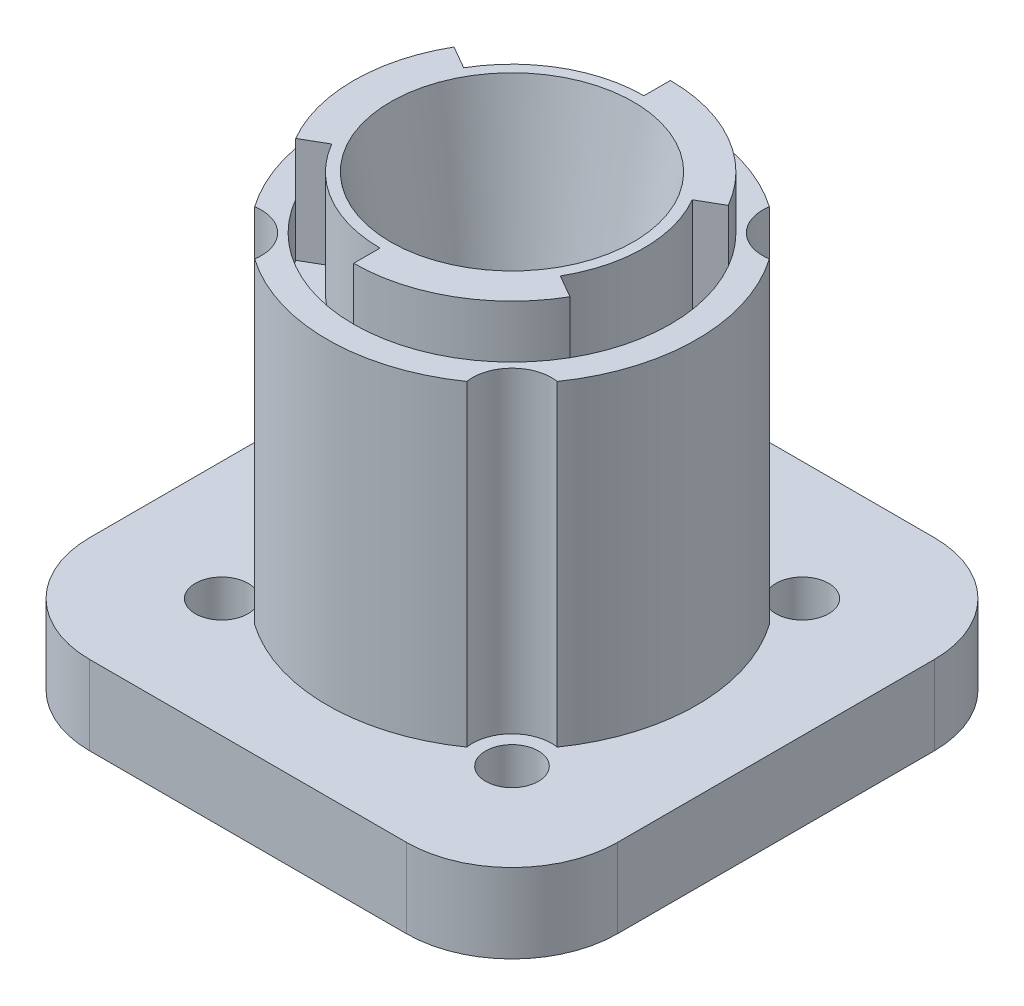
SolidWorks part; units mm, degrees
ref_plane "Alzado" through (0, 0, 0) normal (0, 0, 1) x (1, 0, 0)
ref_plane "Planta" through (0, 0, 0) normal (0, 1, 0) x (1, 0, 0)
ref_plane "Vista lateral" through (0, 0, 0) normal (1, 0, 0) x (0, 0, -1)
sketch "Croquis1" plane through (0, 0, 0) normal (0, 1, 0) x (1, 0, 0)
  line L1 (0, 0) -> (-50, 0)
  line L2 (0, 0) -> (0, -50)
  line L3 (0, -50) -> (-50, -50)
  line L4 (-50, 0) -> (-50, -50)
  dimension "D1" = 50
extrude "Saliente-Extruir1" add sketch "Croquis1" along normal blind 7.5
sketch "Sketch4" plane through (0, 7.5, 0) normal (0, 1, 0) x (1, 0, 0)
  line L0 (0, -50) -> (-50, 0) construction
  line L1 (-50, -50) -> (0, 0) construction
  arc A0 (-39.3299, -14.9549) -> (-39.3299, -35.0451) centre (-25, -25) ccw
  circle A1 centre (-25, -25) radius 12.5
  arc A2 (-14.9549, -10.6701) -> (-10.6701, -14.9549) centre (-11.25, -11.25) ccw
  arc A3 (-39.3299, -35.0451) -> (-35.0451, -39.3299) centre (-38.75, -38.75) cw
  arc A4 (-10.6701, -35.0451) -> (-14.9549, -39.3299) centre (-11.25, -38.75) ccw
  arc A5 (-35.0451, -10.6701) -> (-39.3299, -14.9549) centre (-38.75, -11.25) cw
  arc A6 (-35.0451, -39.3299) -> (-14.9549, -39.3299) centre (-25, -25) ccw
  arc A7 (-10.6701, -35.0451) -> (-10.6701, -14.9549) centre (-25, -25) ccw
  arc A8 (-14.9549, -10.6701) -> (-35.0451, -10.6701) centre (-25, -25) ccw
  dimension "D1" = 35
  dimension "D4" = 7.5
  dimension "D2" = 5
  dimension "D3" = 13.75
  dimension "D5" = 13.75
extrude "Boss-Extrude2" add sketch "Sketch4" along normal blind 30 contours A1 L1 A0 L0 | A1 L0 A0 L1 | A1 L0 A0 L1 | A1 L1 A0 L0
sketch "Sketch5" plane through (0, 7.5, 0) normal (0, 1, 0) x (1, 0, 0)
  line L4 (0, -50) -> (0, 0)
  line L5 (0, 0) -> (-50, 0)
  line L6 (-50, 0) -> (-50, -50)
  line L7 (-50, -50) -> (0, -50)
  line L8 (0, -50) -> (0, 0)
  line L9 (0, 0) -> (-50, 0)
  line L10 (-50, 0) -> (-50, -50)
  line L11 (-50, -50) -> (0, -50)
  arc A0 (-39.3299, -14.9549) -> (-35.0451, -10.6701) centre (-38.75, -11.25) ccw construction
  arc A1 (-39.3299, -14.9549) -> (-35.0451, -10.6701) centre (-38.75, -11.25) ccw
  arc A2 (-35.0451, -39.3299) -> (-39.3299, -35.0451) centre (-38.75, -38.75) ccw construction
  arc A3 (-10.6701, -35.0451) -> (-14.9549, -39.3299) centre (-11.25, -38.75) ccw construction
  arc A4 (-14.9549, -10.6701) -> (-10.6701, -14.9549) centre (-11.25, -11.25) ccw construction
  arc A5 (-35.0451, -39.3299) -> (-39.3299, -35.0451) centre (-38.75, -38.75) ccw
  arc A6 (-10.6701, -35.0451) -> (-14.9549, -39.3299) centre (-11.25, -38.75) ccw
  arc A7 (-14.9549, -10.6701) -> (-10.6701, -14.9549) centre (-11.25, -11.25) ccw
  circle A8 centre (-38.75, -11.25) radius 3.75
  circle A9 centre (-11.25, -11.25) radius 3.75
  circle A10 centre (-11.25, -38.75) radius 3.75
  circle A11 centre (-38.75, -38.75) radius 3.75
  arc M11 (-14.9549, -10.6701) -> (-10.6701, -14.9549) centre (-11.25, -11.25) ccw
  arc M13 (-10.6701, -35.0451) -> (-14.9549, -39.3299) centre (-11.25, -38.75) ccw
  arc M15 (-35.0451, -39.3299) -> (-39.3299, -35.0451) centre (-38.75, -38.75) ccw
  arc M17 (-39.3299, -14.9549) -> (-35.0451, -10.6701) centre (-38.75, -11.25) ccw
  dimension "D1" = 0
extrude "Cut-Extrude1" cut sketch "Sketch5" against normal up to next contours A8 M17 | A9 M11 | A10 M13 | A11 M15
sketch "Sketch6" plane through (0, 0, 0) normal (0, -1, 0) x (1, 0, 0)
  line L0 (-25, 0) -> (-25, 50) construction
  line L1 (0, 0) -> (-50, 0) construction
  line L2 (-50, 50) -> (0, 50) construction
  circle A0 centre (-11.25, 38.75) radius 3.75
  circle A1 centre (-38.75, 38.75) radius 3.75
  circle A2 centre (-38.75, 11.25) radius 3.75
  circle A3 centre (-11.25, 11.25) radius 3.75
  circle A4 centre (-38.75, 38.75) radius 2.5
  circle A5 centre (-38.75, 11.25) radius 2.5
  circle A6 centre (-11.25, 11.25) radius 2.5
  circle A7 centre (-11.25, 38.75) radius 2.5
  dimension "D1" = 5
extrude "Boss-Extrude4" add sketch "Sketch6" against normal blind 7.5
sketch "Sketch7" plane through (0, 37.5, 0) normal (0, 1, 0) x (1, 0, 0)
  line L3 (-35.8253, -18.75) -> (-37.9904, -17.5)
  line L7 (-25, -12.5) -> (-25, -10)
  line L11 (-14.1747, -18.75) -> (-12.0096, -17.5)
  line L19 (-14.1747, -31.25) -> (-12.0096, -32.5)
  line L21 (-25, -37.5) -> (-25, -40)
  line L23 (-35.8253, -31.25) -> (-37.9904, -32.5)
  circle A12 centre (-25, -25) radius 12.5 construction
  arc A22 (-37.9904, -32.5) -> (-25, -40) centre (-25, -25) ccw
  circle A23 centre (-25, -25) radius 12.5 construction
  arc A24 (-35.8253, -31.25) -> (-25, -37.5) centre (-25, -25) ccw
  arc A25 (-25, -12.5) -> (-35.8253, -18.75) centre (-25, -25) ccw
  arc A26 (-25, -10) -> (-37.9904, -17.5) centre (-25, -25) ccw
  arc A27 (-14.1747, -31.25) -> (-14.1747, -18.75) centre (-25, -25) ccw
  arc A28 (-12.0096, -32.5) -> (-12.0096, -17.5) centre (-25, -25) ccw
  point P18 (-26.717, -30)
  point P20 (-25, -25)
  point P21 (-25, -25)
sketch "Sketch9" plane through (0, 37.5, 0) normal (0, 1, 0) x (1, 0, 0)
  line L13 (-35.8253, -18.75) -> (-37.9904, -17.5)
  line L15 (-25, -12.5) -> (-25, -10)
  line L17 (-14.1747, -18.75) -> (-12.0096, -17.5)
  line L19 (-14.1747, -31.25) -> (-12.0096, -32.5)
  line L21 (-25, -37.5) -> (-25, -40)
  line L23 (-35.8253, -31.25) -> (-37.9904, -32.5)
  arc A1 (-25, -40) -> (-12.0096, -32.5) centre (-25, -25) ccw
  circle A19 centre (-25, -25) radius 12.5
  arc A20 (-25, -37.5) -> (-14.1747, -31.25) centre (-25, -25) ccw
  arc A21 (-35.8253, -18.75) -> (-35.8253, -31.25) centre (-25, -25) ccw
  arc A22 (-37.9904, -17.5) -> (-37.9904, -32.5) centre (-25, -25) ccw
  arc A23 (-14.1747, -18.75) -> (-25, -12.5) centre (-25, -25) ccw
  arc A24 (-12.0096, -17.5) -> (-25, -10) centre (-25, -25) ccw
  point P18 (-25, -25)
  dimension "D1" = 0
extrude "Boss-Extrude5" add sketch "Sketch9" along normal blind 5
extrude "Cut-Extrude3" cut sketch "Sketch7" against normal blind 5
fillet "Fillet1" radius 10 4 edges at (-50, 3.75, 50) (0, 3.75, 50) (0, 3.75, 0) (-50, 3.75, 0)
sketch "Sketch10" plane through (0, 7.5, 0) normal (0, 1, 0) x (1, 0, 0)
  line L0 (-25, -21.5) -> (-25, -28.5) construction
  circle A0 centre (-25, -21.5) radius 0.5
  circle A3 centre (-25, -28.5) radius 0.5
  point P6 (-25, -25)
  dimension "D3" = 1
  dimension "D2" = 7
extrude "Cut-Extrude4" cut sketch "Sketch10" against normal up to next
ref_plane "Plane3" through (-25, 0, 0) normal (-1, 0, 0) x (0, 0, 1)
sketch "Sketch12" plane through (-25, 0, 0) normal (-1, 0, 0) x (0, 0, 1)
  line L0 (32.5, 37.5) -> (17.5, 37.5) construction
  line L1 (37.5, 42.5) -> (36.5, 42.5)
  line L2 (25, 37.5) -> (25, -3.9539) construction
  line L3 (36.5, 42.5) -> (32.5, 17.5)
  line L4 (37.5, 7.5) -> (37.5, 42.5)
  line L5 (37.5, 7.5) -> (32.5, 7.5)
  line L6 (32.5, 7.5) -> (32.5, 17.5)
  dimension "D1" = 35
  dimension "D2" = 10
  dimension "D3" = 5
  dimension "D4" = 1
revolve "Revolve1" add sketch "Sketch12" angle 360 about L2
equation "\"lado 1 base\"= 50"
equation "\"D1@Croquis1\"=\"lado 1 base\""
equation "\"altura de base\"=7.5"
equation "\"D1@Saliente-Extruir1\"=\"altura de base\""
equation "\"base 2 diametro\"=40"
equation "\"diametro base tornillo\"=5"
equation "\"alto del cilindro\"= 35"
equation "\"Diametro circulillos\"=1"
equation "\"Ancho de pared\"=5"
equation "\"D2@Sketch4\"=\"Ancho de pared\""
equation "\"Diametro ext cilindro\"=35"
equation "\"D1@Sketch4\"=\"Diametro ext cilindro\""
equation "\"altura del cilindro\"=30"
equation "\"D1@Boss-Extrude2\"=\"altura del cilindro\""
equation "\"tornillo\"=5"
equation "\"D1@Sketch6\"=\"tornillo\""
equation "\"tamaño cables\"=1"
equation "\"D3@Sketch10\"=\"tamaño cables\""
equation "\"tamaño bobina +2\"=7"
equation "\"D2@Sketch10\"=\"tamaño bobina +2\""
